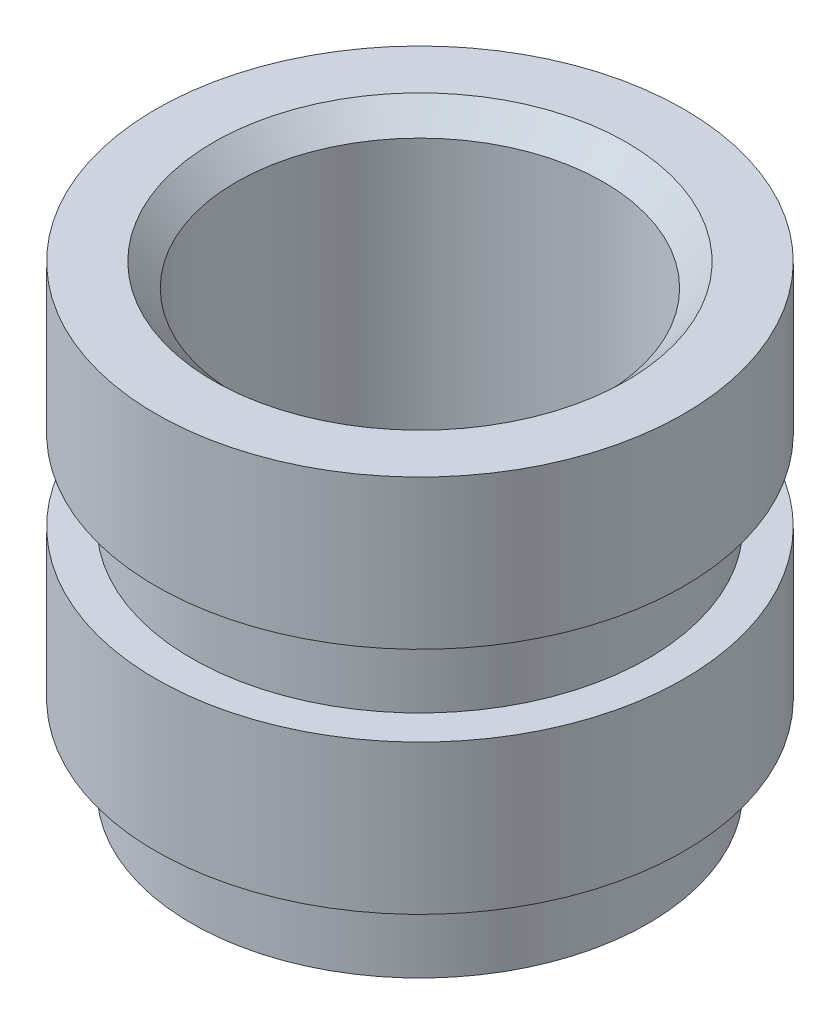
SolidWorks part; units mm, degrees
ref_plane "前视基准面" through (0, 0, 0) normal (0, 0, 1) x (1, 0, 0)
ref_plane "上视基准面" through (0, 0, 0) normal (0, 1, 0) x (1, 0, 0)
ref_plane "右视基准面" through (0, 0, 0) normal (1, 0, 0) x (0, 0, -1)
sketch "草图1" plane through (0, 0, 0) normal (0, 0, 1) x (1, 0, 0)
  line L0 (0, -2.6047) -> (0, 3.6552) construction
  line L1 (-0.8, 1.2084) -> (-1.15, 1.2084)
  line L2 (-1.15, 1.2084) -> (-1.15, 0.5584)
  line L3 (-1.15, 0.5584) -> (-0.9947, 0.5584)
  line L4 (-0.9947, 0.5584) -> (-0.9947, 0.2084)
  line L5 (-0.8, -0.7916) -> (-0.9947, -0.7916)
  line L10 (-0.8, -0.7916) -> (-0.8, 1.2084)
  line L11 (-0.9947, 0.2084) -> (-1.15, 0.2084)
  line L12 (-1.15, 0.2084) -> (-1.15, -0.4416)
  line L13 (-1.15, -0.4416) -> (-0.9947, -0.4416)
  line L14 (-0.9947, -0.4416) -> (-0.9947, -0.7916)
  dimension "D1" = 1.15
  dimension "D2" = 2
  dimension "D3" = 0.65
  dimension "D4" = 0.8
revolve "旋转1" add sketch "草图1" angle 360 about L0
chamfer "倒角1" distance 0.1 angle 45 2 edges at (0, 1.2084, -0.8) (0, -0.7916, -0.8)
